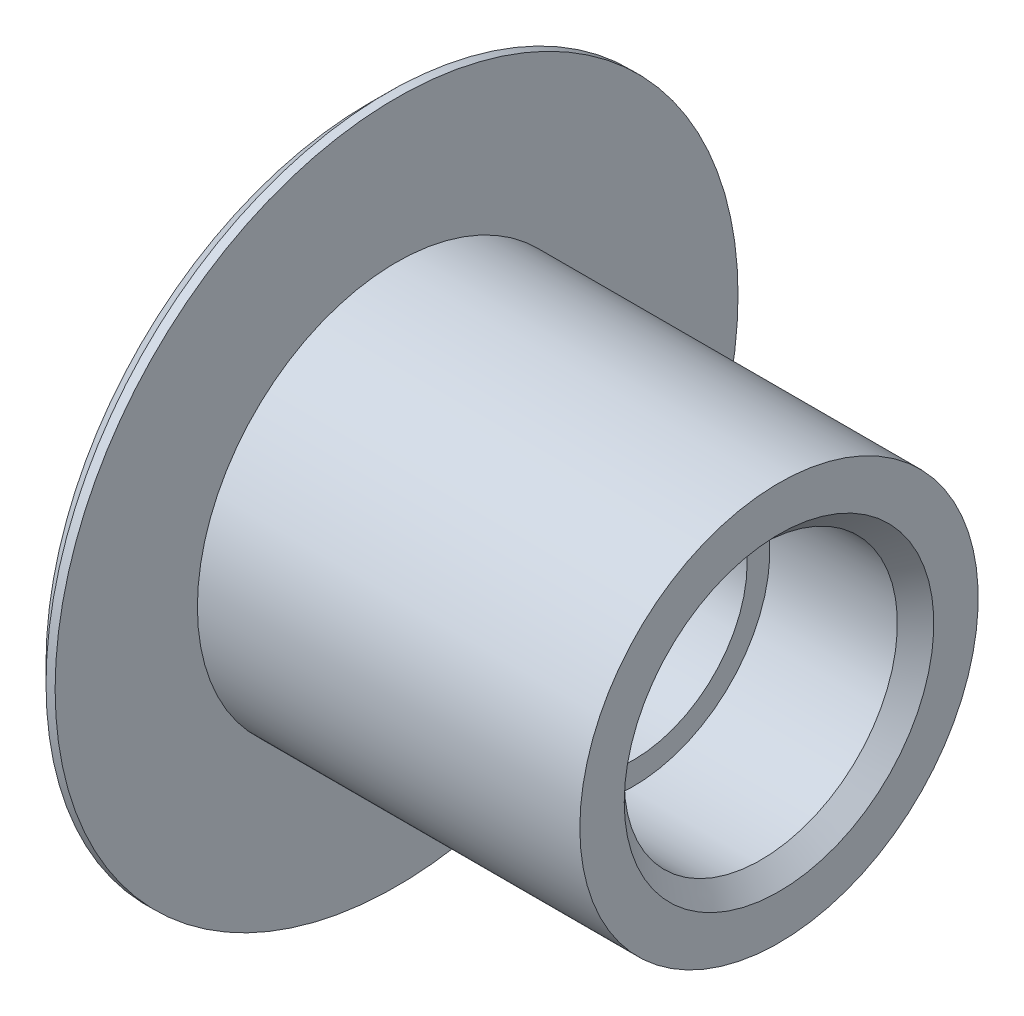
SolidWorks part; units mm, degrees
ref_plane "Front Plane" through (0, 0, 0) normal (0, 0, 1) x (1, 0, 0)
ref_plane "Top Plane" through (0, 0, 0) normal (0, 1, 0) x (1, 0, 0)
ref_plane "Right Plane" through (0, 0, 0) normal (1, 0, 0) x (0, 0, -1)
sketch "Sketch1" plane through (0, 0, 0) normal (0, 0, 1) x (1, 0, 0)
  line L0 (-27.5883, -7.2432) -> (-25.185, -7.2432) construction
  line L1 (-38.5103, 2.2818) -> (-37.7483, 2.2818)
  line L2 (-37.7483, 2.2818) -> (-37.7483, -1.687)
  line L3 (-37.7483, -1.687) -> (-33.4303, -1.687)
  line L4 (-33.4303, -1.687) -> (-27.0803, -1.687)
  line L5 (-31.1443, -3.4332) -> (-27.0803, -3.4332)
  line L6 (-27.0803, -1.687) -> (-27.0803, -3.4332)
  line L7 (-38.5103, 2.2818) -> (-38.5103, -4.0682)
  line L8 (-38.5103, -4.0682) -> (-31.1443, -4.0682)
  line L9 (-31.1443, -3.4332) -> (-31.1443, -4.0682)
  dimension "D1" = 3.9688
  dimension "D2" = 0.762
  dimension "D3" = 6.35
  dimension "D4" = 7.366
  dimension "D5" = 0.635
  dimension "D6" = 4.064
  dimension "D7" = 6.35
revolve "Revolve1" add sketch "Sketch1" angle 360 about L0
chamfer "Chamfer1" distance 0.508 angle 45 3 edges at (-38.5103, -7.2432, 3.175) (-27.0803, -7.2432, 3.81) (-38.5103, -7.2432, 9.525)
